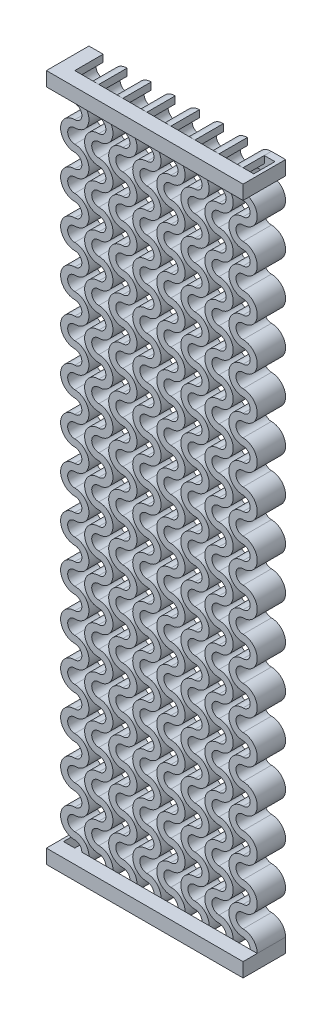
SolidWorks part; units mm, degrees
ref_plane "Front Plane" through (0, 0, 0) normal (0, 0, 1) x (1, 0, 0)
ref_plane "Top Plane" through (0, 0, 0) normal (0, 1, 0) x (1, 0, 0)
ref_plane "Right Plane" through (0, 0, 0) normal (1, 0, 0) x (0, 0, -1)
sketch "Sketch2" plane through (0, 0, 0) normal (0, 0, 1) x (1, 0, 0)
  line L0 (0, 0) -> (0, 8.4344) construction
  line L1 (0, -3.175) -> (0, -1.5875)
  line L4 (0, 150.8125) -> (0, 149.225)
  arc A0 (0, 3.175) -> (0, -3.175) centre (0, 0) cw
  arc A1 (0, 3.175) -> (0, 6.35) centre (0, 4.7625) cw
  arc A2 (0, 6.35) -> (0, 12.7) centre (0, 9.525) ccw
  arc A3 (0, 12.7) -> (0, 15.875) centre (0, 14.2875) cw
  arc A4 (0, 15.875) -> (0, 22.225) centre (0, 19.05) ccw
  arc A5 (0, 22.225) -> (0, 25.4) centre (0, 23.8125) cw
  arc A6 (0, 25.4) -> (0, 31.75) centre (0, 28.575) ccw
  arc A7 (0, 31.75) -> (0, 34.925) centre (0, 33.3375) cw
  arc A8 (0, 1.5875) -> (0, -1.5875) centre (0, 0) cw
  arc A9 (0, 1.5875) -> (0, 7.9375) centre (0, 4.7625) cw
  arc A10 (0, 7.9375) -> (0, 11.1125) centre (0, 9.525) ccw
  arc A11 (0, 11.1125) -> (0, 17.4625) centre (0, 14.2875) cw
  arc A12 (0, 17.4625) -> (0, 20.6375) centre (0, 19.05) ccw
  arc A13 (0, 20.6375) -> (0, 26.9875) centre (0, 23.8125) cw
  arc A14 (0, 26.9875) -> (0, 30.1625) centre (0, 28.575) ccw
  arc A15 (0, 30.1625) -> (0, 36.5125) centre (0, 33.3375) cw
  arc A16 (0, 41.275) -> (0, 44.45) centre (0, 42.8625) cw
  arc A17 (0, 36.5125) -> (0, 39.6875) centre (0, 38.1) ccw
  arc A18 (0, 34.925) -> (0, 41.275) centre (0, 38.1) ccw
  arc A19 (0, 39.6875) -> (0, 46.0375) centre (0, 42.8625) cw
  arc A20 (0, 74.6125) -> (0, 77.7875) centre (0, 76.2) ccw
  arc A21 (0, 50.8) -> (0, 44.45) centre (0, 47.625) cw
  arc A22 (0, 49.2125) -> (0, 55.5625) centre (0, 52.3875) cw
  arc A23 (0, 82.55) -> (0, 88.9) centre (0, 85.725) ccw
  arc A24 (0, 65.0875) -> (0, 68.2625) centre (0, 66.675) ccw
  arc A25 (0, 84.1375) -> (0, 87.3125) centre (0, 85.725) ccw
  arc A26 (0, 88.9) -> (0, 92.075) centre (0, 90.4875) cw
  arc A27 (0, 68.2625) -> (0, 74.6125) centre (0, 71.4375) cw
  arc A28 (0, 63.5) -> (0, 69.85) centre (0, 66.675) ccw
  arc A29 (0, 69.85) -> (0, 73.025) centre (0, 71.4375) cw
  arc A30 (0, 77.7875) -> (0, 84.1375) centre (0, 80.9625) cw
  arc A31 (0, 73.025) -> (0, 79.375) centre (0, 76.2) ccw
  arc A32 (0, 49.2125) -> (0, 46.0375) centre (0, 47.625) cw
  arc A33 (0, 50.8) -> (0, 53.975) centre (0, 52.3875) cw
  arc A34 (0, 55.5625) -> (0, 58.7375) centre (0, 57.15) ccw
  arc A35 (0, 60.325) -> (0, 63.5) centre (0, 61.9125) cw
  arc A36 (0, 79.375) -> (0, 82.55) centre (0, 80.9625) cw
  arc A37 (0, 87.3125) -> (0, 93.6625) centre (0, 90.4875) cw
  arc A38 (0, 53.975) -> (0, 60.325) centre (0, 57.15) ccw
  arc A39 (0, 58.7375) -> (0, 65.0875) centre (0, 61.9125) cw
  arc A40 (0, 134.9375) -> (0, 141.2875) centre (0, 138.1125) cw
  arc A41 (0, 115.8875) -> (0, 122.2375) centre (0, 119.0625) cw
  arc A42 (0, 127) -> (0, 130.175) centre (0, 128.5875) cw
  arc A43 (0, 107.95) -> (0, 111.125) centre (0, 109.5375) cw
  arc A44 (0, 136.525) -> (0, 139.7) centre (0, 138.1125) cw
  arc A45 (0, 96.8375) -> (0, 103.1875) centre (0, 100.0125) cw
  arc A46 (0, 130.175) -> (0, 136.525) centre (0, 133.35) ccw
  arc A47 (0, 120.65) -> (0, 127) centre (0, 123.825) ccw
  arc A48 (0, 103.1875) -> (0, 106.3625) centre (0, 104.775) ccw
  arc A49 (0, 98.425) -> (0, 92.075) centre (0, 95.25) cw
  arc A50 (0, 98.425) -> (0, 101.6) centre (0, 100.0125) cw
  arc A51 (0, 101.6) -> (0, 107.95) centre (0, 104.775) ccw
  arc A52 (0, 117.475) -> (0, 120.65) centre (0, 119.0625) cw
  arc A53 (0, 125.4125) -> (0, 131.7625) centre (0, 128.5875) cw
  arc A54 (0, 96.8375) -> (0, 93.6625) centre (0, 95.25) cw
  arc A55 (0, 106.3625) -> (0, 112.7125) centre (0, 109.5375) cw
  arc A56 (0, 122.2375) -> (0, 125.4125) centre (0, 123.825) ccw
  arc A57 (0, 131.7625) -> (0, 134.9375) centre (0, 133.35) ccw
  arc A58 (0, 112.7125) -> (0, 115.8875) centre (0, 114.3) ccw
  arc A59 (0, 111.125) -> (0, 117.475) centre (0, 114.3) ccw
  arc A60 (0, 146.05) -> (0, 139.7) centre (0, 142.875) cw
  arc A61 (0, 146.05) -> (0, 149.225) centre (0, 147.6375) cw
  arc A62 (0, 144.4625) -> (0, 141.2875) centre (0, 142.875) cw
  arc A63 (0, 144.4625) -> (0, 150.8125) centre (0, 147.6375) cw
  dimension "D1" = 3.175
  dimension "D2" = 1.5875
  dimension "D5" = 1.5875
  dimension "D7" = 3.175
  dimension "D8" = 1.5875
  dimension "D9" = 3.175
  dimension "D10" = 3.175
  dimension "D4" = 9.525
  dimension "D6" = 9.525
  dimension "D3" = 1.5875
extrude "Boss-Extrude1" add sketch "Sketch2" along normal blind 6.35
pattern_linear "LPattern1" count 8 spacing 5.3848 along (1, 0, 0) of bodies 101
sketch "Sketch5" plane through (5.3848, 0, 0) normal (1, 0, 0) x (0, 0, -1)
  line L1 (-6.35, 150.8125) -> (-9.525, 150.8125)
  line L2 (-6.35, 150.8125) -> (-6.35, 147.6375)
  line L3 (-6.35, 147.6375) -> (-9.525, 147.6375)
  line L4 (-9.525, 150.8125) -> (-9.525, 147.6375)
  dimension "D1" = 3.175
  dimension "D2" = 3.175
extrude "Boss-Extrude2" add sketch "Sketch5" against normal through all
sketch "Sketch6" plane through (0, 0, 0) normal (-1, 0, 0) x (0, 0, 1)
  line L1 (6.35, -3.175) -> (9.525, -3.175)
  line L2 (6.35, -3.175) -> (6.35, 0)
  line L3 (6.35, 0) -> (9.525, 0)
  line L4 (9.525, -3.175) -> (9.525, 0)
  dimension "D1" = 3.175
  dimension "D2" = 3.175
extrude "Boss-Extrude3" add sketch "Sketch6" against normal through all
sketch "Sketch8" plane through (0, 0, 6.35) normal (0, 0, -1) x (-1, 0, 0)
  line L2 (3.175, 147.6375) -> (3.175, 150.8125) construction
  line L3 (3.175, 150.8125) -> (0, 150.8125) construction
  line L4 (0, -1.5875) -> (0, 0) construction
  line L5 (0, 0) -> (-1.5875, 0) construction
  line L10 (3.175, 147.6375) -> (3.175, 150.8125)
  line L11 (3.175, 150.8125) -> (0, 150.8125)
  line L12 (0, -1.5875) -> (0, 0)
  line L13 (0, 0) -> (-1.5875, 0)
  line L24 (-40.8686, -3.175) -> (-5.3848, -3.175) construction
  line L25 (-40.8686, 0) -> (-40.8686, -3.175) construction
  line L26 (-40.8686, -3.175) -> (-37.6936, -3.175)
  line L27 (-40.8686, 0) -> (-40.8686, -3.175)
  arc A1 (3.175, 147.6375) -> (0, 150.8125) centre (0, 147.6375) ccw construction
  arc A2 (-1.5875, 0) -> (0, -1.5875) centre (0, 0) ccw construction
  arc A5 (3.175, 147.6375) -> (0, 150.8125) centre (0, 147.6375) ccw
  arc A6 (-1.5875, 0) -> (0, -1.5875) centre (0, 0) ccw
  arc A12 (-37.6936, 3.175) -> (-37.6936, -3.175) centre (-37.6936, 0) ccw construction
  arc A13 (-40.8686, 0) -> (-37.6936, -3.175) centre (-37.6936, 0) ccw
extrude "Boss-Extrude5" add sketch "Sketch8" along normal through all
sketch "Sketch9" plane through (0, 0, 0) normal (-1, 0, 0) x (0, 0, 1)
  line L5 (9.525, 0) -> (0, 0)
  line L6 (0, 0) -> (0, -3.175)
  line L7 (0, -3.175) -> (6.35, -3.175)
  line L8 (6.35, -3.175) -> (9.525, -3.175)
  line L9 (9.525, -3.175) -> (9.525, 0)
  line L10 (9.525, 0) -> (0, 0)
  line L11 (0, 0) -> (0, -3.175)
  line L12 (0, -3.175) -> (6.35, -3.175)
  line L13 (6.35, -3.175) -> (9.525, -3.175)
  line L14 (9.525, -3.175) -> (9.525, 0)
  dimension "D1" = 0
extrude "Boss-Extrude6" add sketch "Sketch9" along normal through all
sketch "Sketch10" plane through (5.3848, 0, 0) normal (1, 0, 0) x (0, 0, -1)
  line L0 (-6.35, 149.225) -> (-6.35, 150.8125)
  line L15 (-9.525, 147.6375) -> (-6.35, 147.6375)
  line L16 (0, 149.225) -> (0, 150.8125)
  line L17 (0, 150.8125) -> (-6.35, 150.8125)
  line L18 (-6.35, 150.8125) -> (-9.525, 150.8125)
  line L19 (-9.525, 150.8125) -> (-9.525, 147.6375)
  line L20 (-9.525, 147.6375) -> (-6.35, 147.6375)
  line L23 (-6.35, 150.8125) -> (-9.525, 150.8125)
  line L24 (-9.525, 150.8125) -> (-9.525, 147.6375)
  line L27 (-6.35, 147.6375) -> (-6.35, 149.225)
  line L28 (-6.35, 147.6375) -> (-6.35, 149.225)
  line L29 (-6.35, 149.225) -> (0, 149.225)
  dimension "D1" = 0
extrude "Boss-Extrude7" add sketch "Sketch10" along normal through all
sketch "Sketch12" plane through (0, -3.175, 0) normal (0, -1, 0) x (1, 0, 0)
  line L0 (-3.175, 0) -> (0, 0) construction
  line L1 (0, 6.35) -> (-2.54, 6.35)
  line L2 (0, 6.35) -> (0, 1.27)
  line L3 (0, 1.27) -> (-2.54, 1.27)
  line L4 (-2.54, 6.35) -> (-2.54, 1.27)
  dimension "D1" = 2.54
  dimension "D2" = 1.27
extrude "Cut-Extrude2" cut sketch "Sketch12" against normal up to next (3.175 mm away)
sketch "Sketch14" plane through (0, 0, 6.35) normal (0, 0, -1) x (-1, 0, 0)
  line L0 (-3.7973, 147.6375) -> (-40.8686, 147.6375) construction
  line L1 (-40.8686, 150.8125) -> (-40.0812, 150.8125)
  line L2 (-40.8686, 150.8125) -> (-40.8686, 147.6375)
  line L3 (-40.8686, 147.6375) -> (-40.0812, 147.6375)
  line L4 (-40.0812, 150.8125) -> (-40.0812, 147.6375)
  dimension "D1" = 0.7874
extrude "Boss-Extrude8" add sketch "Sketch14" along normal up to surface (6.35 mm away)
sketch "Sketch15" plane through (0, 0, 0) normal (0, 0, -1) x (-1, 0, 0)
  line L4 (-37.6936, 150.8125) -> (-40.0812, 150.8125)
  line L5 (-40.0812, 150.8125) -> (-40.0812, 147.6375)
  line L6 (-40.0812, 147.6375) -> (-36.1061, 147.6375)
  line L7 (-37.6936, 149.225) -> (-37.6936, 150.8125)
  line L8 (-37.6936, 150.8125) -> (-40.0812, 150.8125)
  line L9 (-40.0812, 150.8125) -> (-40.0812, 147.6375)
  line L10 (-40.0812, 147.6375) -> (-36.1061, 147.6375)
  line L11 (-37.6936, 149.225) -> (-37.6936, 150.8125)
  arc A1 (-36.1061, 147.6375) -> (-37.6936, 149.225) centre (-37.6936, 147.6375) ccw
  arc A2 (-36.1061, 147.6375) -> (-37.6936, 149.225) centre (-37.6936, 147.6375) ccw
  dimension "D1" = 0
extrude "Boss-Extrude9" add sketch "Sketch15" against normal blind 1.6002
